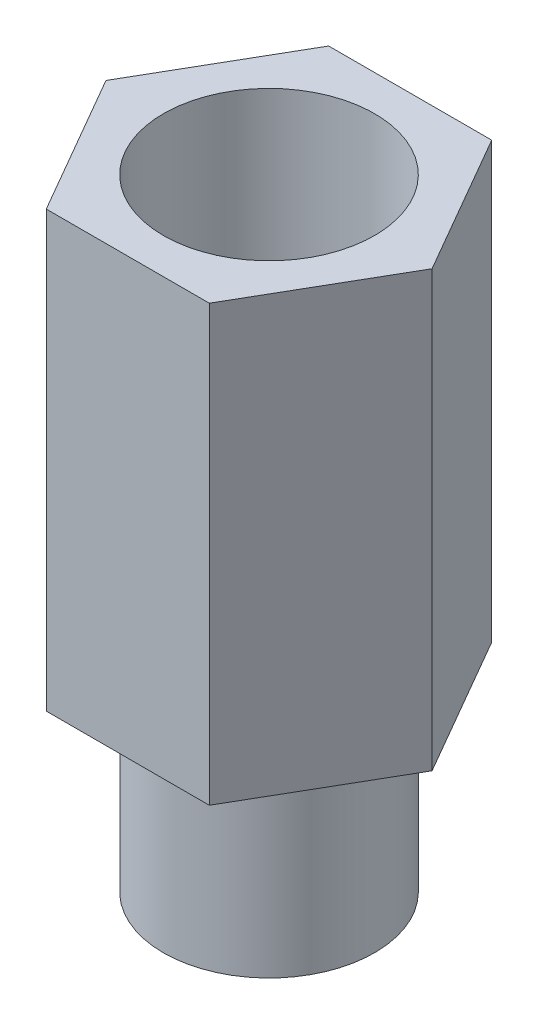
SolidWorks part; units mm, degrees
ref_plane "前视基准面" through (0, 0, 0) normal (0, 0, 1) x (1, 0, 0)
ref_plane "上视基准面" through (0, 0, 0) normal (0, 1, 0) x (1, 0, 0)
ref_plane "右视基准面" through (0, 0, 0) normal (1, 0, 0) x (0, 0, -1)
sketch "草图1" plane through (0, 0, 0) normal (0, 1, 0) x (1, 0, 0)
  line L2 (1.3125, -2.2733) -> (2.625, 0)
  line L4 (1.3125, 2.2733) -> (-1.3125, 2.2733)
  line L5 (-1.3125, 2.2733) -> (-2.625, 0)
  line L6 (1.3125, 2.2733) -> (2.625, 0)
  line L7 (1.3125, -2.2733) -> (-1.3125, -2.2733)
  line L8 (-1.3125, -2.2733) -> (-2.625, 0)
extrude "凸台-拉伸1" add sketch "草图1" along normal blind 7
sketch "草图2" plane through (0, 0, 0) normal (0, 1, 0) x (1, 0, 0)
  circle A0 centre (0, 0) radius 1.7
extrude "凸台-拉伸2" add sketch "草图2" against normal blind 3
sketch "草图3" plane through (0, 7, 0) normal (0, 1, 0) x (1, 0, 0)
  circle A0 centre (0, 0) radius 1.7
extrude "切除-拉伸1" cut sketch "草图3" against normal blind 4
